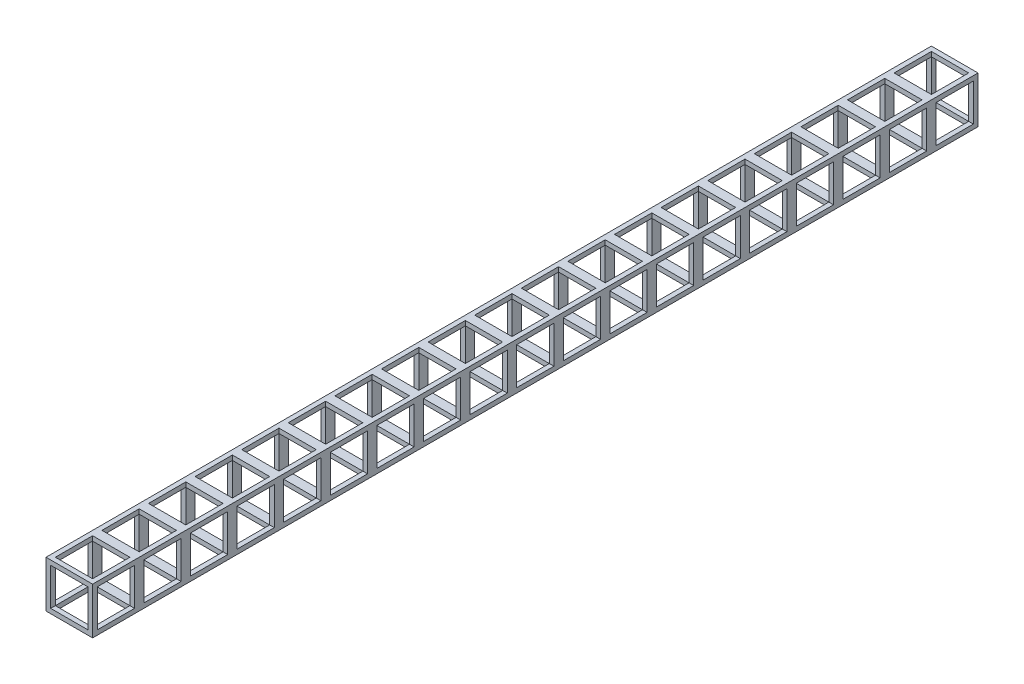
SolidWorks part; units mm, degrees
ref_plane "Ebene vorne" through (0, 0, 0) normal (0, 0, 1) x (1, 0, 0)
ref_plane "Ebene oben" through (0, 0, 0) normal (0, 1, 0) x (1, 0, 0)
ref_plane "Ebene rechts" through (0, 0, 0) normal (1, 0, 0) x (0, 0, -1)
sketch "Skizze1" plane through (0, 0, 0) normal (0, 0, 1) x (1, 0, 0)
  line L1 (0, 0) -> (50, 0)
  line L2 (0, 0) -> (0, 50)
  line L3 (0, 50) -> (50, 50)
  line L4 (50, 0) -> (50, 50)
  dimension "D1" = 50
  dimension "D2" = 50
extrude "Aufsatz-Linear austragen1" add sketch "Skizze1" along normal blind 950
sketch "Skizze2" plane through (0, 0, 0) normal (0, 0, -1) x (-1, 0, 0)
  line L0 (-50, 0) -> (-50, 50) construction
  line L1 (-45, 45) -> (-5, 45)
  line L2 (-45, 45) -> (-45, 5)
  line L3 (-45, 5) -> (-5, 5)
  line L4 (-5, 45) -> (-5, 5)
  line L5 (0, 50) -> (0, 0) construction
  line L6 (-50, 50) -> (0, 50) construction
  line L7 (0, 0) -> (-50, 0) construction
  dimension "D1" = 5
  dimension "D2" = 5
  dimension "D3" = 5
  dimension "D4" = 5
extrude "Schnitt-Linear austragen1" cut sketch "Skizze2" against normal through all
sketch "Skizze3" plane through (0, 0, 0) normal (-1, 0, 0) x (0, 0, 1)
  line L0 (950, 50) -> (0, 50) construction
  line L1 (5, 45) -> (45, 45)
  line L2 (5, 45) -> (5, 5)
  line L3 (5, 5) -> (45, 5)
  line L4 (45, 45) -> (45, 5)
  line L5 (0, 50) -> (0, 0) construction
  dimension "D1" = 40
  dimension "D2" = 40
  dimension "D3" = 5
  dimension "D4" = 5
extrude "Schnitt-Linear austragen2" cut sketch "Skizze3" against normal through all both and the other way through all
pattern_linear "Lineares Muster1" count 19 spacing 50 along (0, 0, 1) of "Schnitt-Linear austragen2"
sketch "Skizze4" plane through (0, 50, 0) normal (0, 1, 0) x (1, 0, 0)
  line L0 (50, 0) -> (0, 0) construction
  line L1 (5, -5) -> (45, -5)
  line L2 (5, -5) -> (5, -45)
  line L3 (5, -45) -> (45, -45)
  line L4 (45, -5) -> (45, -45)
  line L5 (0, -950) -> (0, 0) construction
  dimension "D1" = 40
  dimension "D2" = 40
  dimension "D3" = 5
  dimension "D4" = 5
extrude "Schnitt-Linear austragen3" cut sketch "Skizze4" against normal through all both and the other way through all
pattern_linear "Lineares Muster2" count 19 spacing 50 along (0, 0, 1) of "Schnitt-Linear austragen3"
